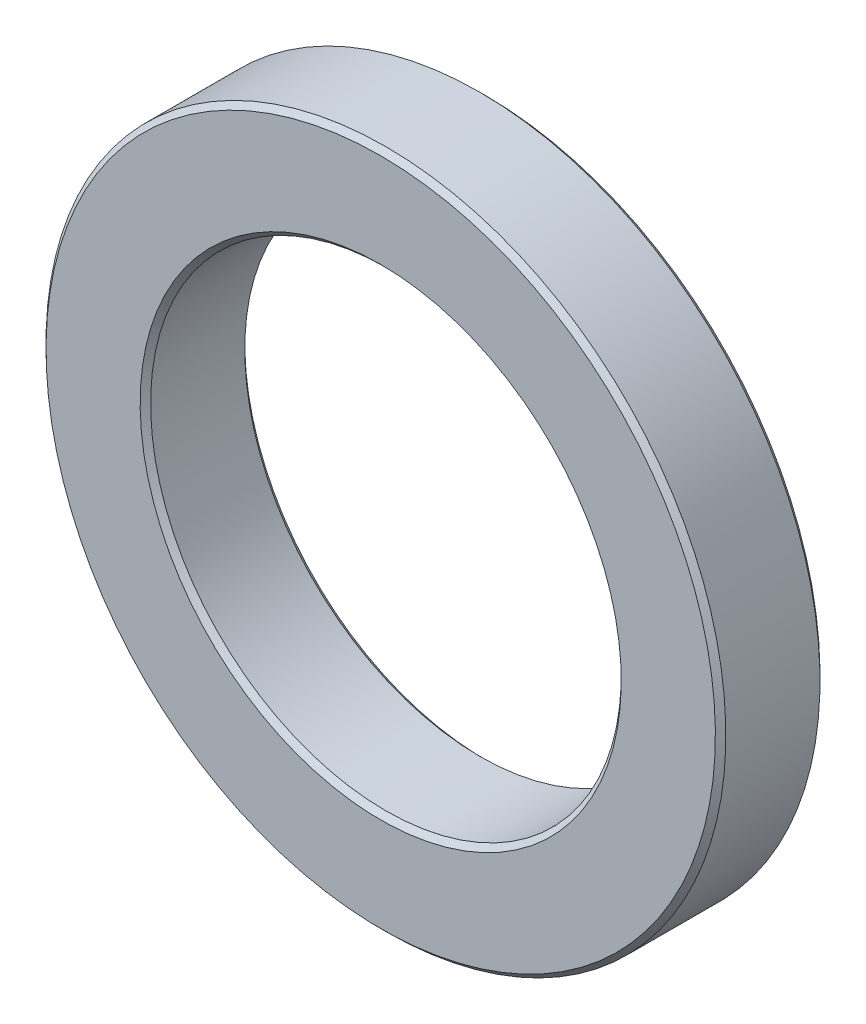
SolidWorks part; units mm, degrees
material "Malleable Cast Iron"
ref_plane "Front Plane" through (0, 0, 0) normal (0, 0, 1) x (1, 0, 0)
ref_plane "Top Plane" through (0, 0, 0) normal (0, 1, 0) x (1, 0, 0)
ref_plane "Right Plane" through (0, 0, 0) normal (1, 0, 0) x (0, 0, -1)
sketch "Sketch1" plane through (0, 0, 0) normal (1, 0, 0) x (0, 0, -1)
  line L0 (0, 0) -> (-60.3088, 0) construction
  line L1 (-9.6375, 32.5) -> (-10.1375, 32)
  line L2 (-0.6375, 22.5) -> (-9.6375, 22.5)
  line L3 (-0.1375, 23) -> (-0.1375, 32)
  line L4 (-0.6375, 32.5) -> (-9.6375, 32.5)
  line L5 (-10.1375, 23) -> (-10.1375, 32)
  line L6 (-0.1375, 32) -> (-0.6375, 32.5)
  line L7 (-0.1375, 23) -> (-0.6375, 22.5)
  line L8 (-9.6375, 22.5) -> (-10.1375, 23)
  point P3 (-0.1375, 22.5)
  point P4 (-10.1375, 32.5)
  point P5 (-0.1375, 32.5)
  point P6 (-10.1375, 22.5)
  dimension "D1" = 45
  dimension "D2" = 65
  dimension "D3" = 10
  dimension "D4" = 0.5
  dimension "D5" = 45
  dimension "D6" = 0.5
  dimension "D7" = 45
  dimension "D8" = 0.5
  dimension "D9" = 45
  dimension "D10" = 0.5
  dimension "D11" = 45
revolve "Revolve1" add sketch "Sketch1" angle 360 about L0
